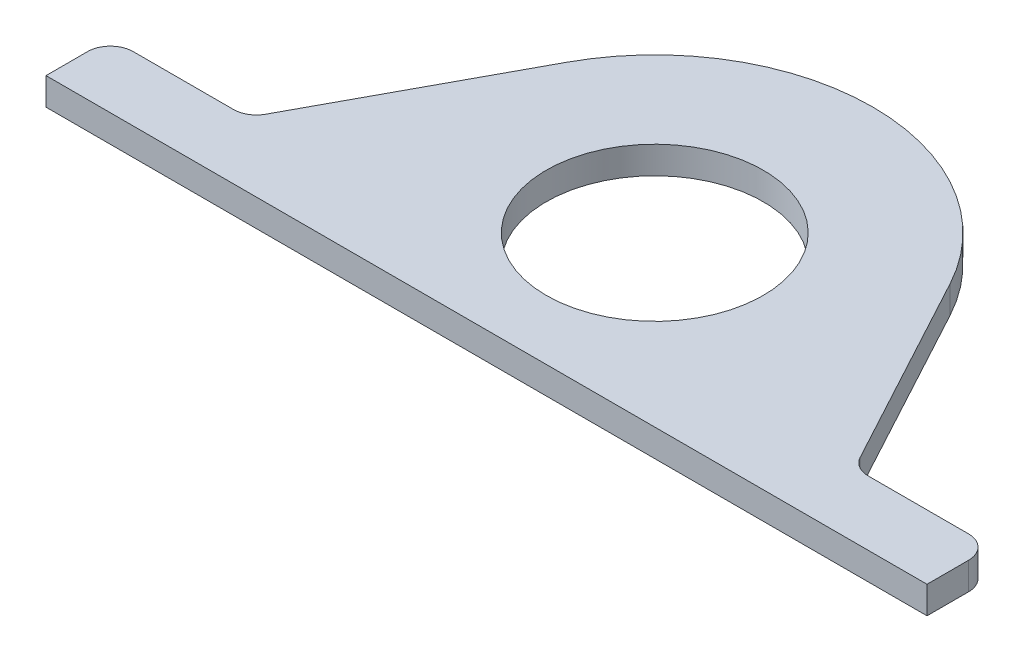
SolidWorks part; units mm, degrees
ref_plane "Front Plane" through (0, 0, 0) normal (0, 0, 1) x (1, 0, 0)
ref_plane "Top Plane" through (0, 0, 0) normal (0, 1, 0) x (1, 0, 0)
ref_plane "Right Plane" through (0, 0, 0) normal (1, 0, 0) x (0, 0, -1)
sketch "Sketch1" plane through (0, 0, 0) normal (0, 1, 0) x (1, 0, 0)
  line L0 (0, 0) -> (0, -23.8) construction
  line L2 (65, -39.8) -> (-65, -39.8)
  line L4 (0, -39.8) -> (0, -23.8) construction
  line L5 (69.5891, -22.7756) -> (91.6057, -22.7756)
  line L6 (-65.1889, -20.15) -> (-42.0661, 22.6998)
  line L7 (42.0661, 22.6998) -> (65.1889, -20.15)
  line L8 (96.6057, -27.7756) -> (96.6057, -39.8)
  line L9 (96.6057, -39.8) -> (65, -39.8)
  line L10 (-96.6057, -27.7756) -> (-96.6057, -39.8)
  line L11 (-69.5891, -22.7756) -> (-91.6057, -22.7756)
  line L12 (-96.6057, -39.8) -> (-65, -39.8)
  circle A0 centre (0, 0) radius 23.8
  arc A1 (42.0661, 22.6998) -> (-42.0661, 22.6998) centre (0, 0) ccw
  arc A2 (91.6057, -22.7756) -> (96.6057, -27.7756) centre (91.6057, -27.7756) cw
  circle A3 centre (0, 0) radius 47.8 construction
  arc A4 (-96.6057, -27.7756) -> (-91.6057, -22.7756) centre (-91.6057, -27.7756) cw
  arc A5 (65.1889, -20.15) -> (69.5891, -22.7756) centre (69.5891, -17.7756) ccw
  arc A6 (-65.1889, -20.15) -> (-69.5891, -22.7756) centre (-69.5891, -17.7756) cw
  point P7 (48, 0)
  point P20 (96.6057, -22.7756)
  point P23 (-96.6057, -22.7756)
  point P26 (66.6057, -22.7756)
  point P29 (-66.6057, -22.7756)
  dimension "D1" = 24
  dimension "D5" = 47.6
  dimension "D7" = 5
  dimension "D2" = 16
  dimension "D3" = 17.1
  dimension "D4" = 130
  dimension "D6" = 30
extrude "Boss-Extrude1" add sketch "Sketch1" along normal blind 6
sketch "Sketch2" plane through (0, 0, 0) normal (0, -1, 0) x (1, 0, 0)
  line L0 (-96.6057, 39.8) -> (96.6057, 39.8) construction
  line L2 (114.691, 45.5914) -> (-125.2278, 45.5914)
  line L3 (114.691, 45.5914) -> (114.691, 36.9)
  line L4 (114.691, 36.9) -> (-125.2278, 36.9)
  line L5 (-125.2278, 45.5914) -> (-125.2278, 36.9)
  dimension "D1" = 2.9
extrude "Cut-Extrude1" cut sketch "Sketch2" against normal blind 10
